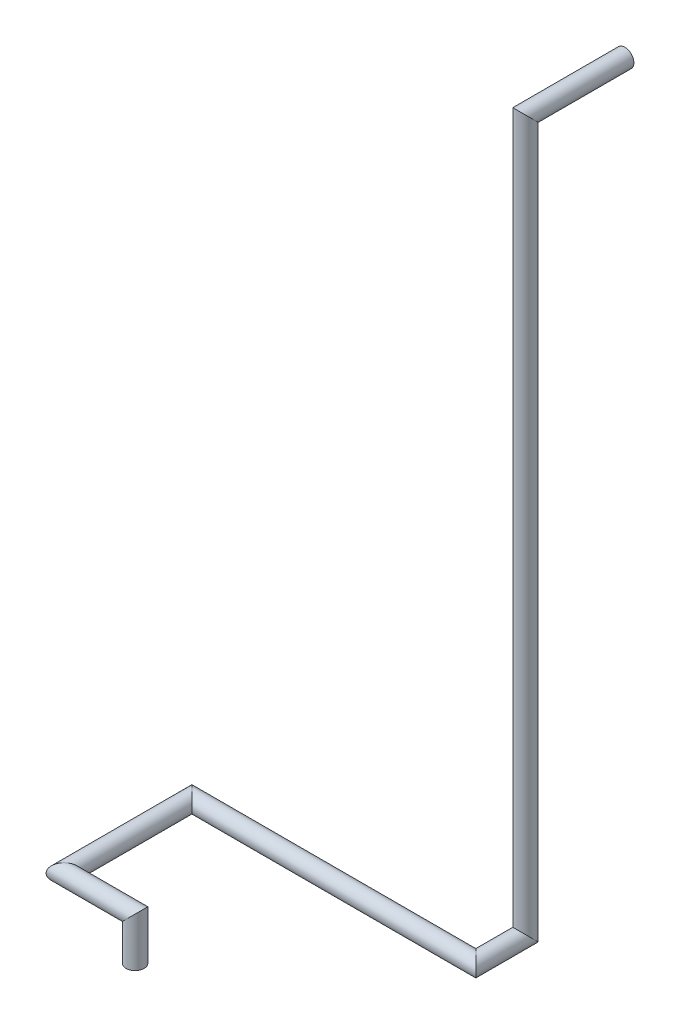
SolidWorks part; units mm, degrees
ref_plane "Alzado" through (0, 0, 0) normal (0, 0, 1) x (1, 0, 0)
ref_plane "Planta" through (0, 0, 0) normal (0, 1, 0) x (1, 0, 0)
ref_plane "Vista lateral" through (0, 0, 0) normal (1, 0, 0) x (0, 0, -1)
sketch "Croquis1" plane through (0, 0, 0) normal (0, 0, 1) x (1, 0, 0)
  circle A0 centre (0, 0) radius 12.7
  dimension "D1" = 25.4
extrude "Saliente-Extruir1" add sketch "Croquis1" along normal blind 50
sketch3d "Croquis3D1"
  line L0 (0, 0, 50) -> (0, 0, 140)
  line L1 (0, 0, 50) -> (0, 0, 0) construction
  line L2 (0, 0, 140) -> (0, -1000, 140)
  line L3 (0, -1000, 140) -> (0, -1000, 210)
  line L4 (0, -1000, 210) -> (-400, -1000, 210)
  line L5 (-400, -1000, 210) -> (-400, -1000, 390)
  line L6 (-400, -1000, 390) -> (-300, -1000, 390)
  line L7 (-300, -1000, 390) -> (-300, -1060, 390)
  dimension "D1" = 90
  dimension "D2" = 1000
  dimension "D3" = 70
  dimension "D4" = 400
  dimension "D5" = 180
  dimension "D6" = 100
  dimension "D7" = 60
sketch "Croquis2" plane through (0, 0, 50) normal (0, 0, 1) x (1, 0, 0)
  circle A0 centre (0, 0) radius 12.7
sweep "Barrer1" add profiles "Croquis2" path "Croquis3D1"
